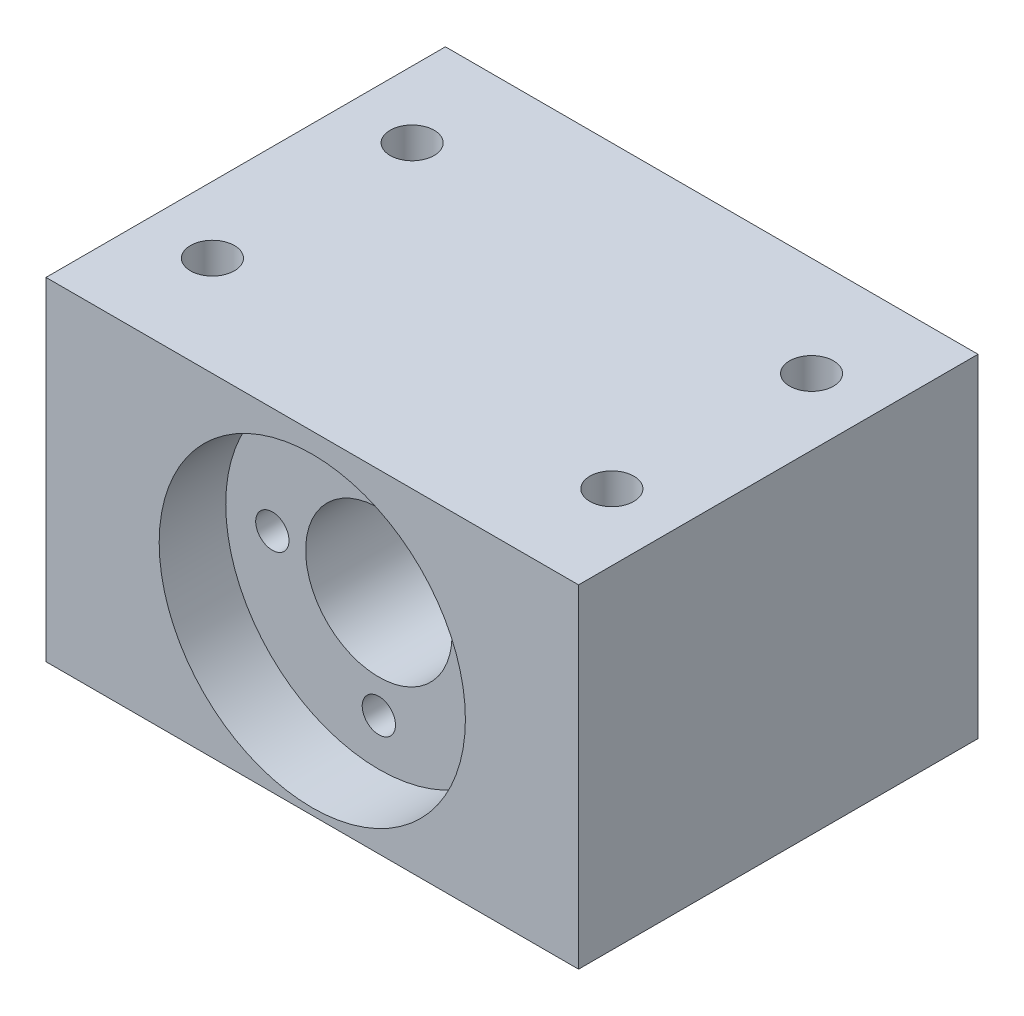
SolidWorks part; units mm, degrees
material "3.3535 (EN-AW 5754)"
ref_plane "Ön Düzlem" through (0, 0, 0) normal (0, 0, 1) x (1, 0, 0)
ref_plane "Üst Düzlem" through (0, 0, 0) normal (0, 1, 0) x (1, 0, 0)
ref_plane "Sağ Düzlem" through (0, 0, 0) normal (1, 0, 0) x (0, 0, -1)
sketch "Sketch1" plane through (0, 0, 0) normal (0, 0, 1) x (1, 0, 0)
  line L0 (-20, 26) -> (-20, 0)
  line L3 (-20, 0) -> (20, 0)
  line L7 (20, 26) -> (-20, 26)
  line L8 (0, -41.6296) -> (0, 41.6296) construction
  line L9 (20, 26) -> (20, 0)
  point P1 (-20, 0)
  point P5 (20, 0)
  point P12 (0, 0)
  dimension "D1" = 26
  dimension "D4" = 40
extrude "Boss-Extrude1" add sketch "Sketch1" along normal mid plane 30
sketch "Sketch2" plane through (0, 0, 15) normal (0, 0, 1) x (1, 0, 0)
  circle A0 centre (0, 13) radius 11.5
  dimension "D1" = 23
  dimension "D2" = 13
extrude "Cut-Extrude1" cut sketch "Sketch2" against normal blind 5
sketch "Sketch3" plane through (0, 0, 10) normal (0, 0, 1) x (1, 0, 0)
  circle A0 centre (0, 13) radius 5.5
  dimension "D1" = 11
extrude "Cut-Extrude2" cut sketch "Sketch3" against normal through all
hole_wizard "M4 Tapped Hole1" positions "Sketch4" profile "Sketch5" tap size "M4" standard "ISO" end condition through all
sketch "Sketch4" plane through (0, 26, 0) normal (0, 1, 0) x (1, 0, 0)
  line L0 (0, 0) -> (-20, 0) construction
  line L1 (-20, -15) -> (-20, 15) construction
  line L3 (0, 0) -> (0, 15) construction
  line L4 (20, 15) -> (-20, 15) construction
  point P0 (-15, 7.5)
  point P2 (15, 7.5)
  point P4 (15, -7.5)
  point P6 (-15, -7.5)
  dimension "D1" = 30
  dimension "D2" = 15
sketch "Sketch5" plane through (-15, 26, -7.5) normal (1, 0, 0) x (0, 0, 1)
  line L0 (0, 0) -> (0, 26)
  line L1 (0, 26) -> (1.65, 26)
  line L2 (1.65, 26) -> (1.65, 0)
  line L5 (1.65, 0) -> (0, 0)
  line L11 (0, -6.35) -> (0, 107.95) construction
  dimension "Thru Tap Drill Dia." = 3.3
  dimension "Thru Tap Drill Depth" = 26
cosmetic thread "Hole Thread5" parameters "D2"=4
cosmetic thread "Hole Thread6" parameters "D2"=4
cosmetic thread "Hole Thread7" parameters "D2"=4
cosmetic thread "Hole Thread8" parameters "D2"=4
sketch "Sketch6" plane through (0, 0, 10) normal (0, 0, 1) x (1, 0, 0)
  circle A0 centre (0, 13) radius 8 construction
  circle A1 centre (0, 21) radius 1.25
  circle A2 centre (9, 13) radius 1.25
  circle A3 centre (1, 4) radius 1.25
  circle A4 centre (-8, 12) radius 1.25
  point P14 (0.5, 12.5)
  dimension "D1" = 16
  dimension "D2" = 2.5
  dimension "D3" = 4
extrude "Cut-Extrude3" [suppressed] cut sketch "Sketch6" against normal through all
hole_wizard "M3 Tapped Hole2" positions "Sketch7" profile "Sketch8" tap size "M3" standard "ISO" end condition through all
sketch "Sketch7" plane through (0, 0, 10) normal (0, 0, 1) x (1, 0, 0)
  line L1 (0, 5) -> (0, 21) construction
  line L5 (8, 13) -> (-8, 13) construction
  circle A0 centre (0, 13) radius 8 construction
  point P11 (0, 21)
  point P76 (0, 5)
  point P77 (0, 13)
  point P87 (-8, 13)
  point P137 (8, 13)
  point P138 (0, 13)
  dimension "D2" = 16
  dimension "D1" = 13
sketch "Sketch8" plane through (0, 13, 10) normal (1, 0, 0) x (0, -1, 0)
  line L0 (0, 0) -> (0, 25)
  line L1 (0, 25) -> (1.25, 25)
  line L2 (1.25, 25) -> (1.25, 0)
  line L5 (1.25, 0) -> (0, 0)
  line L11 (0, -6.35) -> (0, 107.95) construction
  dimension "Thru Tap Drill Dia." = 2.5
  dimension "Thru Tap Drill Depth" = 25
cosmetic thread "Hole Thread1" parameters "D2"=3
cosmetic thread "Hole Thread2" parameters "D2"=3
cosmetic thread "Hole Thread3" parameters "D2"=3
cosmetic thread "Hole Thread4" parameters "D2"=3
sketch "Sketch9" plane through (0, 0, 15) normal (0, 0, 1) x (1, 0, 0)
  line L0 (20, 0) -> (20, 26) construction
  line L1 (-20, 0) -> (20, 0)
  line L2 (-20, 0) -> (-20, 1)
  line L3 (-20, 1) -> (20, 1)
  line L4 (20, 0) -> (20, 1)
  dimension "D1" = 1
extrude "Cut-Extrude4" cut sketch "Sketch9" against normal through all
